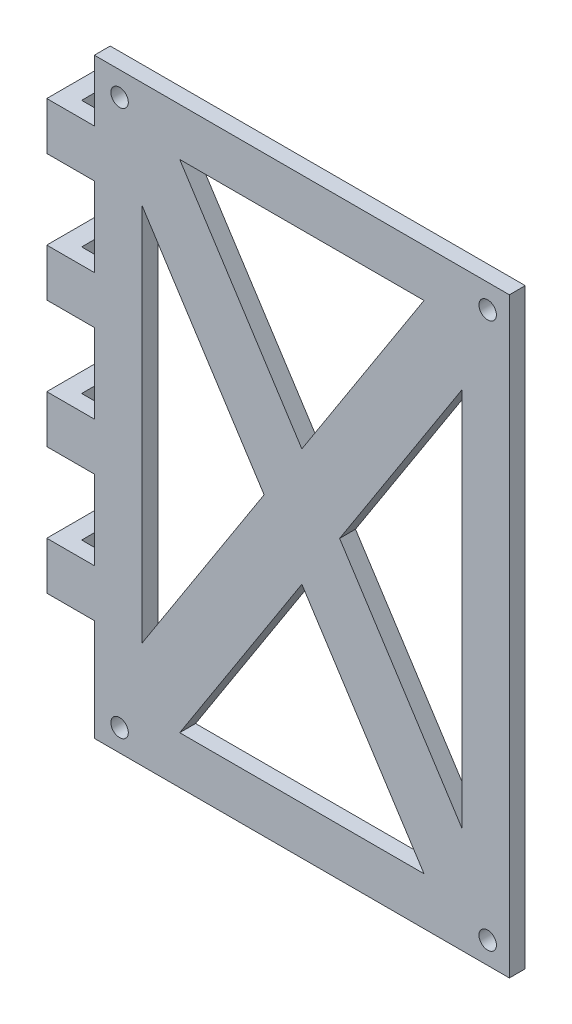
SolidWorks part; units mm, degrees
ref_plane "Front Plane" through (0, 0, 0) normal (0, 0, 1) x (1, 0, 0)
ref_plane "Top Plane" through (0, 0, 0) normal (0, 1, 0) x (1, 0, 0)
ref_plane "Right Plane" through (0, 0, 0) normal (1, 0, 0) x (0, 0, -1)
other "PLA"
sketch "Sketch1" plane through (0, 0, 0) normal (0, 0, 1) x (1, 0, 0)
  line L1 (-45, -50) -> (45, -50)
  line L2 (-45, -50) -> (-45, 50)
  line L3 (-45, 50) -> (45, 50)
  line L4 (45, -50) -> (45, 50)
  line L5 (-45, -50) -> (45, 50) construction
  line L6 (-45, 50) -> (45, -50) construction
  point P0 (0, 0)
  dimension "D1" = 90
  dimension "D2" = 100
extrude "Boss-Extrude1" add sketch "Sketch1" along normal mid plane 2.5
sketch "Sketch3" plane through (0, 0, -1.25) normal (0, 0, -1) x (-1, 0, 0)
  line L0 (35.1161, 29.3256) -> (35.1161, 16.8256)
  line L1 (-30.279, 46.4899) -> (35.1161, 46.4899)
  line L2 (-30.279, 46.4899) -> (-30.279, -46.7398)
  line L3 (-30.279, -46.7398) -> (35.1161, -46.7398)
  line L4 (35.1161, 46.4899) -> (35.1161, 36.8256)
  line L9 (35.1161, 36.8256) -> (42.6161, 36.8256)
  line L10 (42.6161, 36.8256) -> (42.6161, 29.3256)
  line L11 (42.6161, 29.3256) -> (35.1161, 29.3256)
  line L12 (35.1161, 16.8256) -> (42.6161, 16.8256)
  line L13 (42.6161, 16.8256) -> (42.6161, 9.3256)
  line L14 (42.6161, 9.3256) -> (35.1161, 9.3256)
  line L15 (35.1161, -3.1744) -> (42.6161, -3.1744)
  line L16 (42.6161, -3.1744) -> (42.6161, -10.6744)
  line L17 (42.6161, -10.6744) -> (35.1161, -10.6744)
  line L18 (35.1161, -23.1744) -> (42.6161, -23.1744)
  line L19 (35.1161, -33.9021) -> (35.1161, -46.7398)
  line L20 (42.6161, -23.1744) -> (42.6161, -30.6744)
  line L21 (42.6161, -30.6744) -> (35.1161, -30.6744)
  line L22 (35.1161, 29.3256) -> (35.1161, 16.8256) construction
  line L23 (35.1161, 9.3256) -> (35.1161, -3.1744)
  line L24 (35.1161, -10.6744) -> (35.1161, -23.1744)
  line L25 (35.1161, -30.6744) -> (35.1161, -33.9021)
  line L27 (-16.8314, 38.9899) -> (21.6685, 38.9899)
  line L28 (-22.779, 29.7572) -> (-22.779, -30.0071)
  line L29 (-16.8314, -39.2398) -> (21.6685, -39.2398)
  line L30 (27.6161, 29.7572) -> (27.6161, -30.0071)
  line L31 (-53.6681, 60.63) -> (66.8561, 60.63)
  line L32 (-22.779, 29.7572) -> (-3.5291, -0.1249)
  line L33 (-16.8314, -39.2398) -> (2.4185, -9.3576)
  line L34 (-16.8314, 38.9899) -> (2.4185, 9.1078)
  line L35 (-22.779, -30.0071) -> (-3.5291, -0.1249)
  line L36 (-53.6681, 60.63) -> (-53.6681, -60.4709)
  line L37 (-53.6681, -60.4709) -> (66.8561, -60.4709)
  line L38 (66.8561, 60.63) -> (66.8561, -60.4709)
  line L39 (2.4185, 9.1078) -> (21.6685, 38.9899)
  line L43 (8.3662, -0.1249) -> (27.6161, -30.0071)
  line L44 (8.3662, -0.1249) -> (27.6161, 29.7572)
  line L46 (2.4185, -9.3576) -> (21.6685, -39.2398)
  point P4 (34.0224, -0.4584)
  point P5 (34.0224, -0.4584)
  line M25 (-45, 50) -> (-45, -50)
  line M26 (-45, -50) -> (45, -50)
  line M27 (45, -50) -> (45, 50)
  line M28 (45, 50) -> (-45, 50)
  dimension "D1" = 7.5
  dimension "D2" = 7.5
  dimension "D6" = 7.5
  dimension "D7" = 7.5
  dimension "D8" = 7.5
  dimension "D9" = 7.5
  dimension "D3" = 4
extrude "Cut-Extrude2" cut sketch "Sketch3" against normal through all both and the other way through all contours L38 L31 L36 L37 M25 M28 M27 M26 | L21 L25 L19 L3 L2 L1 L4 L9 L10 L11 L0 L12 L13 L14 L23 L15 L16 L17 L24 L18 L20 M28 M25 M26 M27 | L34 L39 L27 | L28 L35 L32 | L46 L33 L29 | L44 L43 L30
sketch "Sketch4" plane through (0, 0, -1.25) normal (0, 0, -1) x (-1, 0, 0)
  line L0 (42.6161, 29.3256) -> (35.1161, 29.3256) construction
  line L1 (42.6161, 36.8256) -> (39.6161, 36.8256)
  line L2 (42.6161, 36.8256) -> (42.6161, 29.3256)
  line L3 (42.6161, 29.3256) -> (39.6161, 29.3256)
  line L4 (39.6161, 36.8256) -> (39.6161, 29.3256)
  line L5 (42.6161, 16.8256) -> (39.6161, 16.8256)
  line L6 (39.6161, 16.8256) -> (39.6161, 9.3256)
  line L7 (42.6161, 16.8256) -> (42.6161, 9.3256)
  line L8 (42.6161, 9.3256) -> (39.6161, 9.3256)
  line L9 (42.6161, -3.1744) -> (39.6161, -3.1744)
  line L10 (39.6161, -3.1744) -> (39.6161, -10.6744)
  line L11 (42.6161, -3.1744) -> (42.6161, -10.6744)
  line L12 (42.6161, -10.6744) -> (39.6161, -10.6744)
  line L13 (42.6161, -23.1744) -> (39.6161, -23.1744)
  line L14 (39.6161, -23.1744) -> (39.6161, -30.6744)
  line L15 (42.6161, -23.1744) -> (42.6161, -30.6744)
  line L16 (42.6161, -30.6744) -> (39.6161, -30.6744)
  dimension "D1" = 3
  dimension "D2" = 4
extrude "Boss-Extrude2" add sketch "Sketch4" along normal blind 10 and the other way blind 1
sketch "Sketch6" plane through (-39.6161, 0, 0) normal (1, 0, 0) x (0, 0, -1)
  line L0 (1.25, 36.8256) -> (11.25, 36.8256) construction
  line L1 (11.25, 16.8256) -> (7.5, 16.8256)
  line L2 (11.25, 9.3256) -> (11.25, 16.8256)
  line L3 (7.5, 9.3256) -> (11.25, 9.3256)
  line L4 (11.25, -3.1744) -> (7.5, -3.1744)
  line L5 (11.25, -10.6744) -> (11.25, -3.1744)
  line L6 (7.5, -10.6744) -> (11.25, -10.6744)
  line L7 (11.25, -23.1744) -> (7.5, -23.1744)
  line L8 (11.25, -30.6744) -> (11.25, -23.1744)
  line L9 (11.25, 36.8256) -> (1.25, 36.8256)
  line L10 (1.25, 36.8256) -> (1.25, 29.3256)
  line L11 (1.25, 29.3256) -> (11.25, 29.3256)
  line L12 (11.25, 29.3256) -> (11.25, 36.8256)
  line L13 (11.25, 36.8256) -> (7.5, 36.8256)
  line L15 (7.5, 29.3256) -> (11.25, 29.3256)
  line L16 (11.25, 29.3256) -> (11.25, 36.8256)
  line L17 (7.5, -30.6744) -> (11.25, -30.6744)
  arc A1 (7.5, 36.8256) -> (7.5, 29.3256) centre (7.5, 33.0756) cw
  circle A2 centre (6.5685, 33.0756) radius 1.5
  circle A3 centre (6.5685, 13.0756) radius 1.5
  arc A4 (7.5, 16.8256) -> (7.5, 9.3256) centre (7.5, 13.0756) cw
  circle A5 centre (6.5685, -6.9244) radius 1.5
  arc A6 (7.5, -3.1744) -> (7.5, -10.6744) centre (7.5, -6.9244) cw
  circle A7 centre (6.5685, -26.9244) radius 1.5
  arc A8 (7.5, -23.1744) -> (7.5, -30.6744) centre (7.5, -26.9244) cw
  line M5 (11.25, 36.8256) -> (1.25, 36.8256)
  line M7 (1.25, 29.3256) -> (11.25, 29.3256)
  line M8 (11.25, 29.3256) -> (11.25, 36.8256)
  dimension "D2" = 4
  dimension "D1" = 0
extrude "Cut-Extrude4" cut sketch "Sketch6" against normal through all both and the other way through all contours A2 | A1 L16 M5 | A1 M8 M7 | A3 | L2 A4 L3 | L1 A4 L2 | L4 A6 L5 | A5 | L5 A6 L6 | L8 A8 L17 | A7 | L7 A8 L8
sketch "Sketch11" plane through (0, 0, 1.25) normal (0, 0, 1) x (1, 0, 0)
  circle A0 centre (-31.1419, -43.2777) radius 1.375 construction
  circle A1 centre (-31.1419, 42.7223) radius 1.375
  circle A2 centre (26.8581, 42.7223) radius 1.375
  circle A3 centre (26.8581, -43.2777) radius 1.375
  circle A4 centre (-31.1419, -43.2777) radius 1.375
  dimension "D1" = 2.75
extrude "Holder_Screw" cut sketch "Sketch11" against normal through all both and the other way through all
